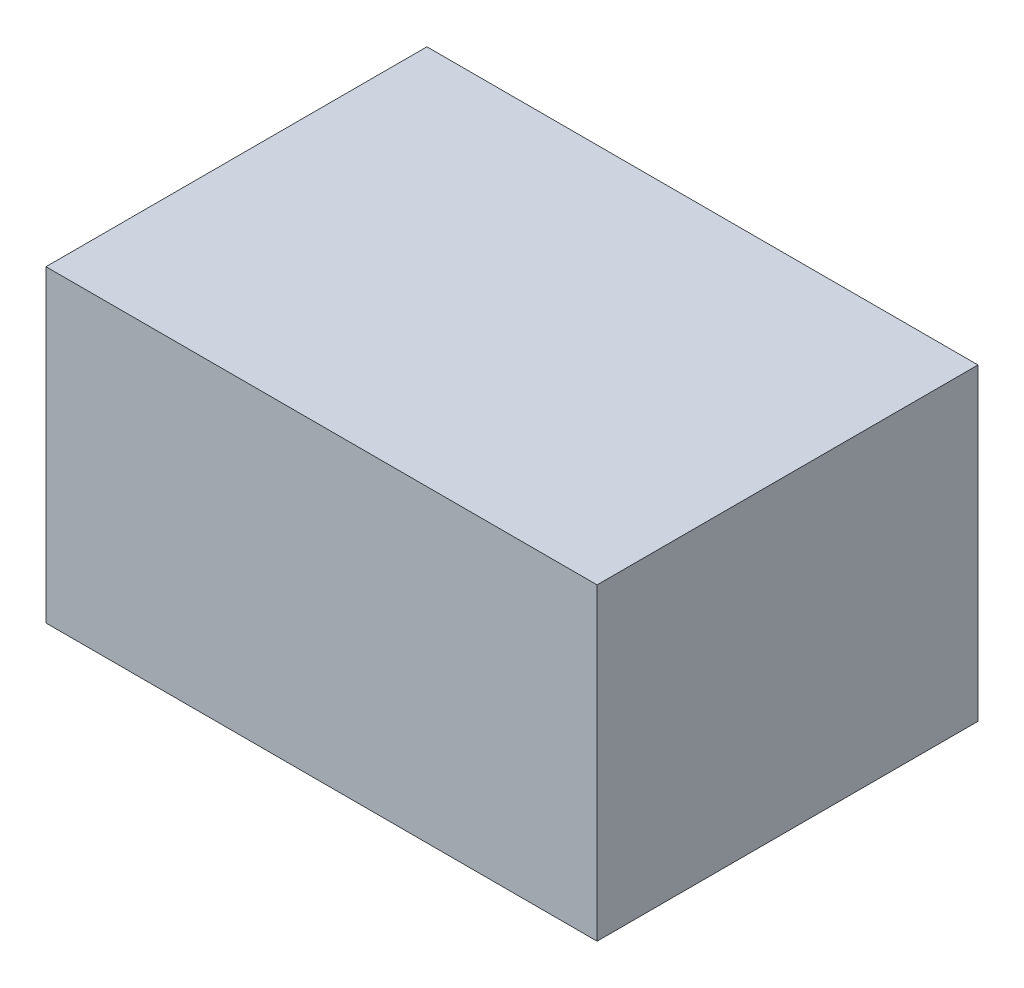
SolidWorks part; units mm, degrees
ref_plane "Front Plane" through (0, 0, 0) normal (0, 0, 1) x (1, 0, 0)
ref_plane "Top Plane" through (0, 0, 0) normal (0, 1, 0) x (1, 0, 0)
ref_plane "Right Plane" through (0, 0, 0) normal (1, 0, 0) x (0, 0, -1)
sketch "Sketch1" plane through (0, 0, 0) normal (0, 0, 1) x (1, 0, 0)
  line L0 (-3.75, 4.75) -> (8.75, 4.75)
  line L1 (8.75, 4.75) -> (8.75, -2.25)
  line L2 (8.75, -2.25) -> (-3.75, -2.25)
  line L3 (-3.75, -2.25) -> (-3.75, 4.75)
extrude "Component_Outline" add sketch "Sketch1" along normal blind 8.64 separate body
sketch3d "3DSketch1"
  line L0 (0, 0, 0) -> (1, 0, 0)
  line L1 (0, 0, 0) -> (0, 1, 0)
  line L2 (0, 0, 0) -> (0, 0, 1)
  point P0 (0, 0, 0)
